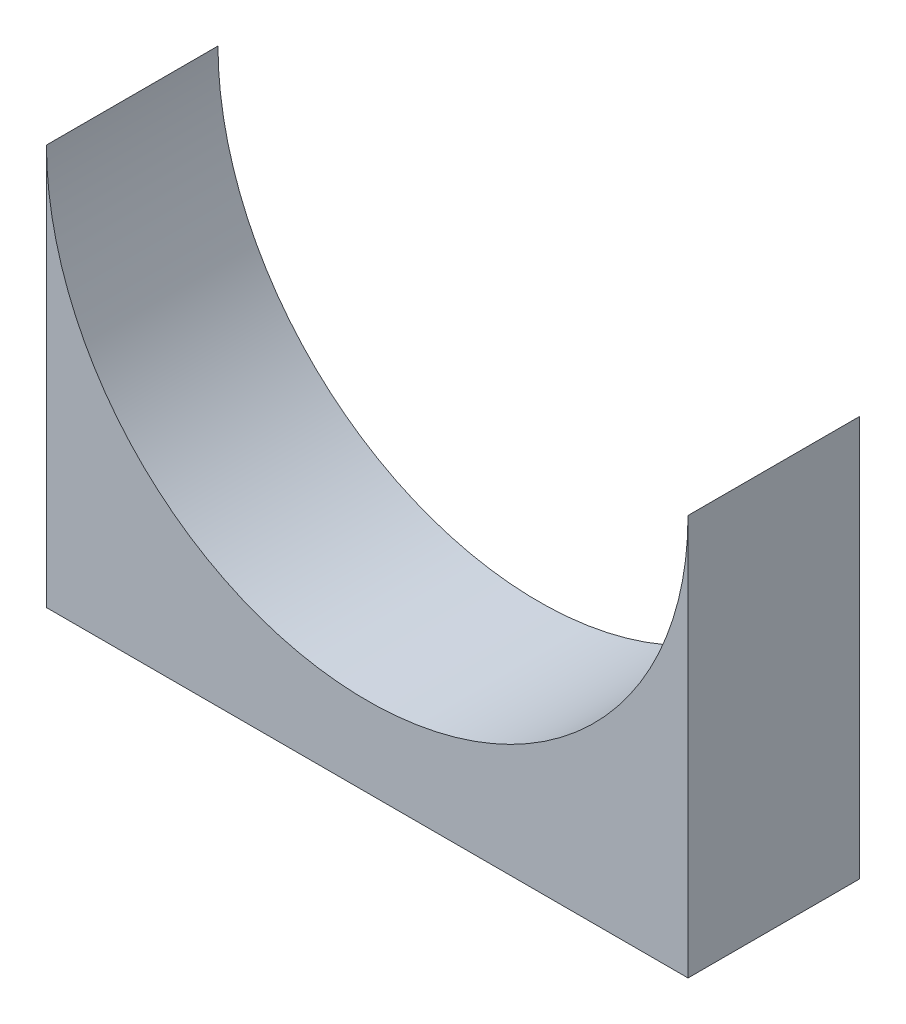
SolidWorks part; units mm, degrees
ref_plane "Front Plane" through (0, 0, 0) normal (0, 0, 1) x (1, 0, 0)
ref_plane "Top Plane" through (0, 0, 0) normal (0, 1, 0) x (1, 0, 0)
ref_plane "Right Plane" through (0, 0, 0) normal (1, 0, 0) x (0, 0, -1)
sketch "Sketch1" plane through (0, 0, 0) normal (0, 0, 1) x (1, 0, 0)
  line L0 (-18.7, 11.6749) -> (-18.7, -11.6749)
  line L1 (-18.7, -11.6749) -> (18.7, -11.6749)
  line L2 (18.7, -11.6749) -> (18.7, 11.6749)
  arc A0 (-18.7, 11.6749) -> (18.7, 11.6749) centre (0, 11.6749) ccw
  dimension "D1" = 18.7
extrude "Boss-Extrude1" add sketch "Sketch1" along normal blind 10
